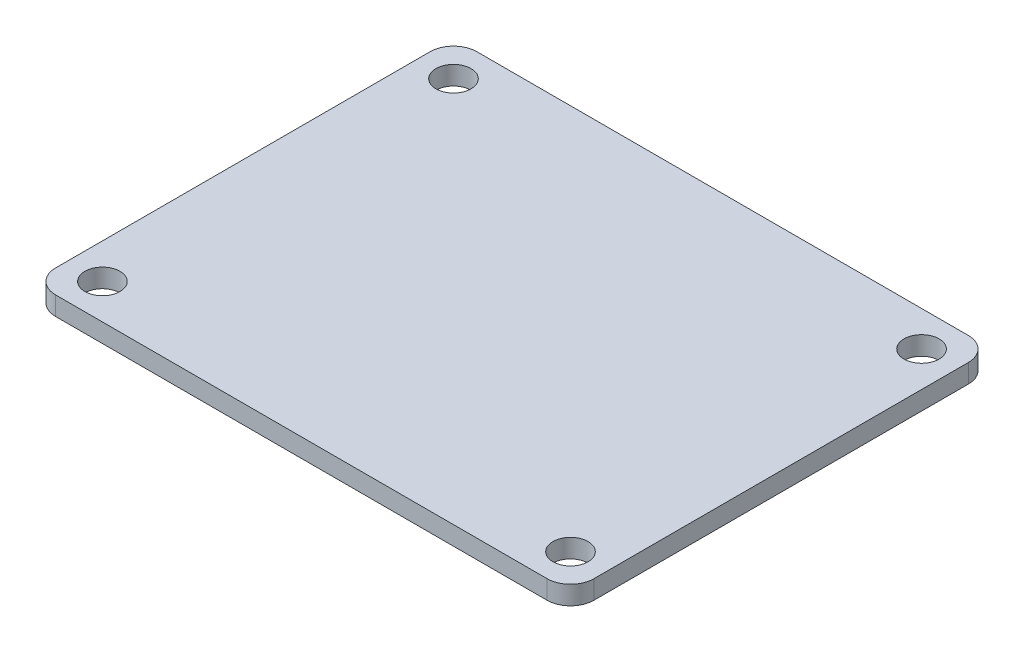
SolidWorks part; units mm, degrees
ref_plane "前视基准面" through (0, 0, 0) normal (0, 0, 1) x (1, 0, 0)
ref_plane "上视基准面" through (0, 0, 0) normal (0, 1, 0) x (1, 0, 0)
ref_plane "右视基准面" through (0, 0, 0) normal (1, 0, 0) x (0, 0, -1)
sketch "Sketch1" plane through (0, 0, 0) normal (0, 1, 0) x (1, 0, 0)
  line L0 (-23, 18) -> (-23, -18)
  line L1 (-20, 15) -> (20, 15) construction
  line L2 (-20, 15) -> (-20, -15) construction
  line L3 (-20, -15) -> (20, -15) construction
  line L4 (20, 15) -> (20, -15) construction
  line L5 (-20, 15) -> (20, -15) construction
  line L6 (-20, -15) -> (20, 15) construction
  line L7 (-23, -18) -> (23, -18)
  line L8 (23, 18) -> (23, -18)
  line L9 (-23, 18) -> (23, 18)
  line L10 (0, 0) -> (0, 7.143) construction
  line L11 (0, 0) -> (6.551, 0) construction
  circle A0 centre (-20, 15) radius 1.5
  circle A1 centre (20, 15) radius 1.5
  circle A2 centre (-20, -15) radius 1.5
  circle A3 centre (20, -15) radius 1.5
  point P0 (0, 0)
  dimension "D2" = 3
  dimension "D1" = 3
  dimension "D3" = 40
  dimension "D4" = 30
extrude "Boss-Extrude1" add sketch "Sketch1" along normal blind 1.6
fillet "Fillet1" radius 2 4 edges at (-23, 0.8, 18) (-23, 0.8, -18) (23, 0.8, -18) (23, 0.8, 18)
